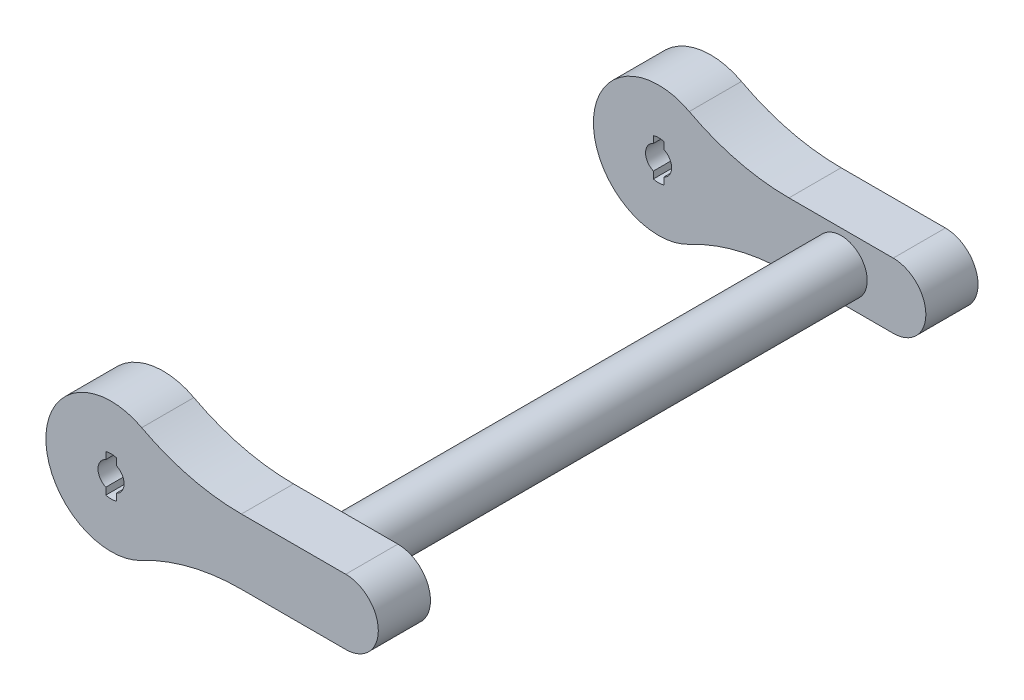
SolidWorks part; units mm, degrees
material "PTFE (general)"
ref_plane "Front Plane" through (0, 0, 0) normal (0, 0, 1) x (1, 0, 0)
ref_plane "Top Plane" through (0, 0, 0) normal (0, 1, 0) x (1, 0, 0)
ref_plane "Right Plane" through (0, 0, 0) normal (1, 0, 0) x (0, 0, -1)
sketch "Sketch1" plane through (0, 0, 0) normal (0, 0, 1) x (1, 0, 0)
  line L0 (90, 12.5) -> (50, 12.5)
  line L1 (90, -12.5) -> (50, -12.5)
  arc A0 (11.7647, 22.0588) -> (11.7647, -22.0588) centre (0, 0) ccw
  arc A1 (90, -12.5) -> (90, 12.5) centre (90, 0) ccw
  arc A2 (50, 12.5) -> (11.7647, 22.0588) centre (50, 93.75) cw
  arc A3 (50, -12.5) -> (11.7647, -22.0588) centre (50, -93.75) ccw
  point P11 (-1.9512, -37.6187)
  dimension "D1" = 50
  dimension "D2" = 25
  dimension "D3" = 40
  dimension "D4" = 90
extrude "Boss-Extrude1" add sketch "Sketch1" along normal blind 20
sketch "Sketch2" plane through (0, 0, 20) normal (0, 0, 1) x (1, 0, 0)
  circle A0 centre (0, 0) radius 5
  dimension "D1" = 10
extrude "Cut-Extrude1" cut sketch "Sketch2" against normal up to surface (20 mm away) up to face at (46.348, 0, 0)
sketch "Sketch5" plane through (0, 0, 20) normal (0, 0, 1) x (1, 0, 0)
  line L4 (-2, 7.2284) -> (-2, -7.2284)
  line L6 (2, -7.2284) -> (2, 7.2284)
  line L8 (0, 7.5) -> (0, -7.5) construction
  arc A0 (-2, -7.2284) -> (2, -7.2284) centre (0, 0) ccw
  arc A1 (2, 7.2284) -> (-2, 7.2284) centre (0, 0) ccw
  point P10 (2, 0)
  point P11 (0, 0)
  point P12 (0, 0)
  dimension "D2" = 15
  dimension "D1" = 4
extrude "Cut-Extrude2" cut sketch "Sketch5" against normal up to surface (20 mm away) up to face at (5, 0, 0)
sketch "Sketch6" plane through (0, 0, 20) normal (0, 0, 1) x (1, 0, 0)
  circle A0 centre (70, 0) radius 10
  dimension "D2" = 20
  dimension "D1" = 70
extrude "Boss-Extrude2" add sketch "Sketch6" along normal blind 95
mirror "Mirror1" about plane through (70, 0, 115) normal (0, 0, 1) of bodies 104
sketch "Sketch7" plane through (0, 0, 0) normal (0, 0, -1) x (-1, 0, 0)
  line L0 (25, 0) -> (-102.5, 0) construction
  line L1 (0, 25) -> (0, -25) construction
  arc A0 (-11.7647, -22.0588) -> (-11.7647, 22.0588) centre (0, 0) ccw construction
  arc A1 (-90, 12.5) -> (-90, -12.5) centre (-90, 0) ccw construction
